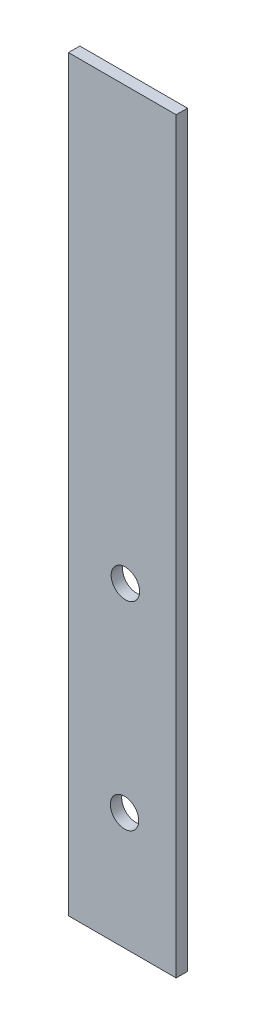
SolidWorks part; units mm, degrees
ref_plane "Front Plane" through (0, 0, 0) normal (0, 0, 1) x (1, 0, 0)
ref_plane "Top Plane" through (0, 0, 0) normal (0, 1, 0) x (1, 0, 0)
ref_plane "Right Plane" through (0, 0, 0) normal (1, 0, 0) x (0, 0, -1)
sketch "Sketch1" plane through (0, 0, 0) normal (0, 0, 1) x (1, 0, 0)
  line L3 (-231.3654, 198.5943) -> (-193.4654, 198.5943)
  line L4 (-193.4654, 198.5943) -> (-193.4654, -64.4965)
  line L5 (-193.4654, -64.4965) -> (-231.3654, -64.4965)
  line L6 (-231.3654, -64.4965) -> (-231.3654, 198.5943)
  circle A2 centre (-211.6343, -23.1738) radius 5
  circle A3 centre (-211.3424, 46.8262) radius 5
  dimension "D2" = 10
  dimension "D3" = 10
  dimension "D1" = 70
  dimension "D4" = 37.9
extrude "Boss-Extrude1" add sketch "Sketch1" along normal blind 4
